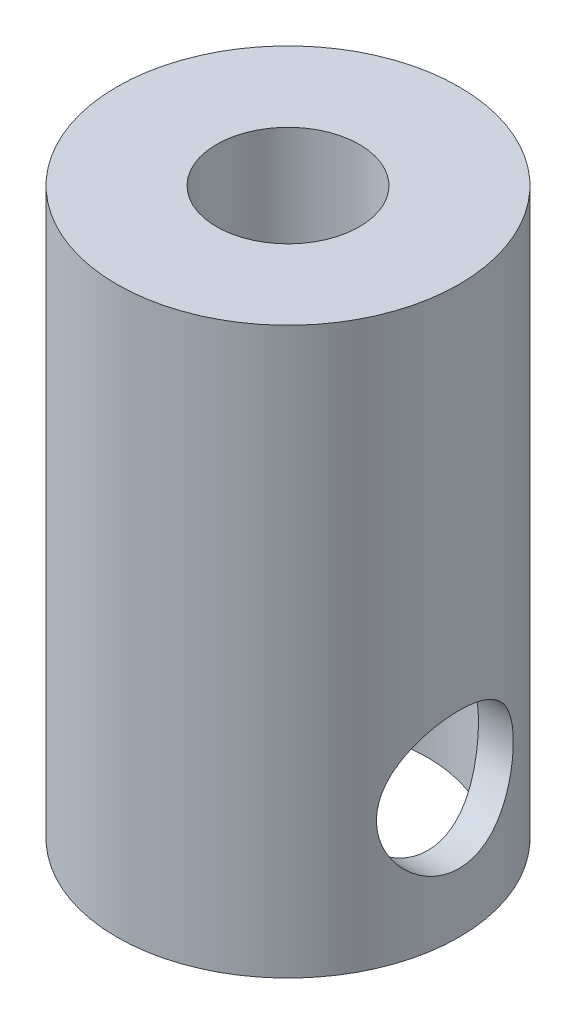
SolidWorks part; units mm, degrees
ref_plane "Front Plane" through (0, 0, 0) normal (0, 0, 1) x (1, 0, 0)
ref_plane "Top Plane" through (0, 0, 0) normal (0, 1, 0) x (1, 0, 0)
ref_plane "Right Plane" through (0, 0, 0) normal (1, 0, 0) x (0, 0, -1)
sketch "Sketch1" plane through (0, 0, 0) normal (0, 1, 0) x (1, 0, 0)
  circle A0 centre (0, 0) radius 4.7
  circle A1 centre (0, 0) radius 5.75
  dimension "D1" = 9.4
  dimension "D2" = 11.5
extrude "Boss-Extrude1" add sketch "Sketch1" along normal blind 10
sketch "Sketch2" plane through (0, 0, 0) normal (1, 0, 0) x (0, 0, -1)
  line L0 (4.7, 10) -> (-4.7, 10) construction
  circle A0 centre (0, 4.3) radius 2.3
  dimension "D1" = 4.6
  dimension "D2" = 5.7
extrude "Cut-Extrude1" cut sketch "Sketch2" against normal through all both and the other way through all
sketch "Sketch3" plane through (0, 10, 0) normal (0, 1, 0) x (1, 0, 0)
  circle A0 centre (0, 0) radius 5.75
  circle A1 centre (0, 0) radius 5.75 construction
extrude "Boss-Extrude2" add sketch "Sketch3" along normal blind 9 contours A0
sketch "Sketch4" plane through (0, 10, 0) normal (0, -1, 0) x (1, 0, 0)
  circle A1 centre (0, 0) radius 4.7
  circle A2 centre (0, 0) radius 4.7
  dimension "D1" = 0
extrude "Boss-Extrude3" add sketch "Sketch4" along normal blind 0.5 contours A2
sketch "Sketch5" plane through (0, 19, 0) normal (0, 1, 0) x (1, 0, 0)
  circle A0 centre (0, 0) radius 2.4
  dimension "D1" = 4.8
extrude "Cut-Extrude2" cut sketch "Sketch5" against normal blind 4.5 and the other way through all
